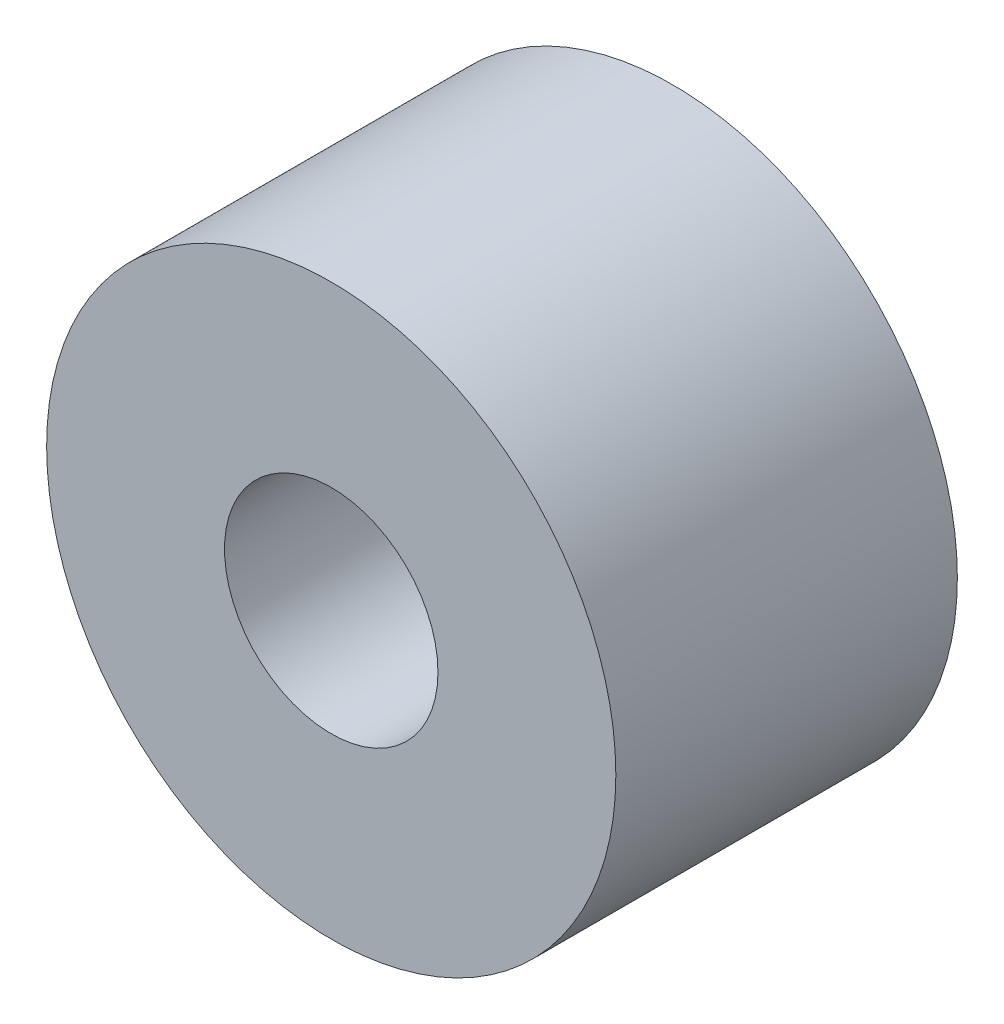
SolidWorks part; units mm, degrees
ref_plane "Front Plane" through (0, 0, 0) normal (0, 0, 1) x (1, 0, 0)
ref_plane "Top Plane" through (0, 0, 0) normal (0, 1, 0) x (1, 0, 0)
ref_plane "Right Plane" through (0, 0, 0) normal (1, 0, 0) x (0, 0, -1)
sketch "Sketch1" plane through (0, 0, 0) normal (0, 1, 0) x (1, 0, 0)
  line L0 (0, 0) -> (0, 21.6884) construction
  line L1 (-12.7, 15.24) -> (-12.7, 0)
  line L2 (-12.7, 15.24) -> (-4.7625, 15.24)
  line L3 (-12.7, 0) -> (-4.7625, 0)
  line L5 (-4.7625, 15.24) -> (-4.7625, 0)
  point P5 (0, 0)
  dimension "D1" = 25.4
  dimension "D2" = 15.24
  dimension "D3" = 9.525
revolve "Revolve1" add sketch "Sketch1" angle 360 about L0
